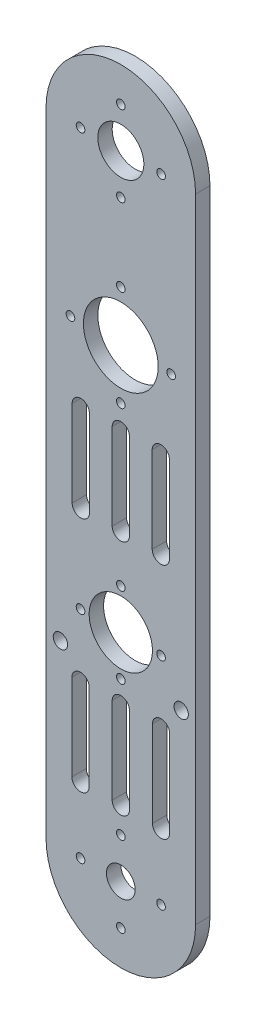
SolidWorks part; units mm, degrees
material "6061 合金"
ref_plane "前视基准面" through (0, 0, 0) normal (0, 0, 1) x (1, 0, 0)
ref_plane "上视基准面" through (0, 0, 0) normal (0, 1, 0) x (1, 0, 0)
ref_plane "右视基准面" through (0, 0, 0) normal (1, 0, 0) x (0, 0, -1)
other "质心 (COM)"
sketch "草图1" plane through (0, 0, 0) normal (0, 0, 1) x (1, 0, 0)
  line L0 (0, 0) -> (0, 110) construction
  line L1 (-26, 220) -> (-26, 0)
  line L4 (-58.7183, 110) -> (53.7841, 110) construction
  line L6 (26, 220) -> (26, 0)
  line L11 (0, 220) -> (0, 161.5) construction
  line L23 (21, 62) -> (21, 110) construction
  line L87 (-21, 62) -> (-21, 110) construction
  line L88 (0, 105.5) -> (0, 135.5) construction
  line L95 (-31.1577, 62) -> (32.7845, 62) construction
  line L99 (2.4, 40.8) -> (18.4, 52.8) construction
  line L100 (20, 40) -> (20, 52) construction
  line L101 (3, 39) -> (19, 39) construction
  line L102 (3.1504, 36.0012) -> (19.1504, 36.0012) construction
  line L103 (2.5504, 34.2012) -> (18.5504, 22.2012) construction
  line L104 (20.1504, 35.0012) -> (20.1504, 23.0012) construction
  line L111 (-2.5504, 34.2012) -> (-18.5504, 22.2012) construction
  line L112 (-20.1504, 35.0012) -> (-20.1504, 23.0012) construction
  line L113 (-3.1504, 36.0012) -> (-19.1504, 36.0012) construction
  line L119 (20, 136) -> (20, 148) construction
  line L120 (2.4, 136.8) -> (18.4, 148.8) construction
  line L121 (-20, 136) -> (-20, 148) construction
  line L122 (20, 131) -> (20, 119) construction
  line L123 (-2.4, 136.8) -> (-18.4, 148.8) construction
  line L124 (3, 132) -> (19, 132) construction
  line L125 (2.4, 130.2) -> (18.4, 118.2) construction
  line L126 (-3, 135) -> (-19, 135) construction
  line L127 (-3, 132) -> (-19, 132) construction
  line L128 (-20, 131) -> (-20, 119) construction
  line L129 (-2.4, 130.2) -> (-18.4, 118.2) construction
  line L130 (3, 135) -> (19, 135) construction
  line L137 (-3, 105.5) -> (-3, 135.5)
  line L140 (3, 105.5) -> (3, 135.5)
  line L143 (0, 23.0012) -> (0, 53.0012) construction
  line L145 (0, 23.0012) -> (0, 53.0012) construction
  line L146 (-3, 23.0012) -> (-3, 53.0012)
  line L147 (3, 23.0012) -> (3, 53.0012)
  line L148 (0, 23.0012) -> (-14, 23.0012) construction
  line L149 (-14, 23.0012) -> (-14, 53.0012) construction
  line L152 (-17, 23.0012) -> (-17, 53.0012)
  line L153 (-11, 23.0012) -> (-11, 53.0012)
  line L154 (14, 23.0012) -> (14, 53.0012) construction
  line L155 (17, 23.0012) -> (17, 53.0012)
  line L156 (11, 23.0012) -> (11, 53.0012)
  line L157 (0, 105.5) -> (0, 135.5) construction
  line L158 (0, 105.5) -> (-13.9136, 105.5) construction
  line L159 (-13.9136, 105.5) -> (-13.9136, 135.5) construction
  line L160 (-16.9136, 105.5) -> (-16.9136, 135.5)
  line L161 (-10.9136, 105.5) -> (-10.9136, 135.5)
  line L162 (13.9136, 105.5) -> (13.9136, 135.5) construction
  line L163 (16.9136, 105.5) -> (16.9136, 135.5)
  line L164 (10.9136, 105.5) -> (10.9136, 135.5)
  arc A0 (-26, 0) -> (26, 0) centre (0, 0) ccw
  circle A3 centre (0, 0) radius 5
  circle A5 centre (0, 0) radius 14 construction
  circle A6 centre (0, -14) radius 1.5
  circle A11 centre (0, 220) radius 22 construction
  circle A14 centre (0, 242) radius 2 construction
  circle A15 centre (0, 220) radius 8
  arc A16 (-26, 220) -> (26, 220) centre (0, 220) cw
  circle A22 centre (-14, 0) radius 1.5
  circle A23 centre (0, 14) radius 1.5
  circle A24 centre (14, 0) radius 1.5
  circle A28 centre (22, 220) radius 2 construction
  circle A29 centre (0, 198) radius 2 construction
  circle A30 centre (-22, 220) radius 2 construction
  circle A32 centre (-21, 62) radius 2.5
  circle A33 centre (21, 62) radius 2.5
  arc A106 (2.4, 40.8) -> (3, 39) centre (3, 40) ccw construction
  arc A107 (20, 52) -> (18.4, 52.8) centre (19, 52) ccw construction
  arc A108 (19, 39) -> (20, 40) centre (19, 40) ccw construction
  arc A109 (2.5504, 34.2012) -> (3.1504, 36.0012) centre (3.1504, 35.0012) cw construction
  arc A110 (20.1504, 23.0012) -> (18.5504, 22.2012) centre (19.1504, 23.0012) cw construction
  arc A111 (19.1504, 36.0012) -> (20.1504, 35.0012) centre (19.1504, 35.0012) cw construction
  arc A118 (-2.5504, 34.2012) -> (-3.1504, 36.0012) centre (-3.1504, 35.0012) ccw construction
  arc A119 (-20.1504, 23.0012) -> (-18.5504, 22.2012) centre (-19.1504, 23.0012) ccw construction
  arc A120 (-19.1504, 36.0012) -> (-20.1504, 35.0012) centre (-19.1504, 35.0012) ccw construction
  circle A143 centre (0, 161.5) radius 5.5 construction
  circle A148 centre (0, 75) radius 14 construction
  circle A149 centre (0, 89) radius 1.5
  circle A153 centre (0, 161.5) radius 13
  circle A154 centre (0, 75) radius 11
  circle A155 centre (0, 220) radius 14 construction
  circle A156 centre (0, 234) radius 1.5
  circle A157 centre (14, 220) radius 1.5
  circle A158 centre (0, 206) radius 1.5
  circle A159 centre (-14, 220) radius 1.5
  circle A160 centre (0, 161.5) radius 17.5 construction
  circle A165 centre (0, 179) radius 1.5
  circle A166 centre (17.5, 161.5) radius 1.5
  circle A167 centre (0, 144) radius 1.5
  circle A168 centre (-17.5, 161.5) radius 1.5
  circle A169 centre (14, 75) radius 1.5
  circle A170 centre (0, 61) radius 1.5
  circle A171 centre (-14, 75) radius 1.5
  arc A174 (-2.4, 136.8) -> (-3, 135) centre (-3, 136) cw construction
  arc A175 (-2.4, 130.2) -> (-3, 132) centre (-3, 131) ccw construction
  arc A176 (19, 135) -> (20, 136) centre (19, 136) ccw construction
  arc A177 (-20, 148) -> (-18.4, 148.8) centre (-19, 148) cw construction
  arc A178 (-20, 119) -> (-18.4, 118.2) centre (-19, 119) ccw construction
  arc A179 (2.4, 130.2) -> (3, 132) centre (3, 131) cw construction
  arc A180 (-19, 135) -> (-20, 136) centre (-19, 136) cw construction
  arc A181 (-19, 132) -> (-20, 131) centre (-19, 131) ccw construction
  arc A182 (20, 119) -> (18.4, 118.2) centre (19, 119) cw construction
  arc A183 (2.4, 136.8) -> (3, 135) centre (3, 136) ccw construction
  arc A184 (20, 148) -> (18.4, 148.8) centre (19, 148) ccw construction
  arc A185 (19, 132) -> (20, 131) centre (19, 131) cw construction
  arc A194 (-3, 23.0012) -> (3, 23.0012) centre (0, 23.0012) ccw
  arc A195 (3, 53.0012) -> (-3, 53.0012) centre (0, 53.0012) ccw
  arc A198 (-17, 23.0012) -> (-11, 23.0012) centre (-14, 23.0012) ccw
  arc A199 (-11, 53.0012) -> (-17, 53.0012) centre (-14, 53.0012) ccw
  arc A200 (17, 23.0012) -> (11, 23.0012) centre (14, 23.0012) cw
  arc A201 (11, 53.0012) -> (17, 53.0012) centre (14, 53.0012) cw
  arc A202 (-3, 105.5) -> (3, 105.5) centre (0, 105.5) ccw
  arc A203 (3, 135.5) -> (-3, 135.5) centre (0, 135.5) ccw
  arc A204 (-16.9136, 105.5) -> (-10.9136, 105.5) centre (-13.9136, 105.5) ccw
  arc A205 (-10.9136, 135.5) -> (-16.9136, 135.5) centre (-13.9136, 135.5) ccw
  arc A206 (16.9136, 105.5) -> (10.9136, 105.5) centre (13.9136, 105.5) cw
  arc A207 (10.9136, 135.5) -> (16.9136, 135.5) centre (13.9136, 135.5) cw
  point P48 (0, 220)
  point P51 (0, 0)
  point P55 (0, 220)
  point P58 (0, 120.5)
  point P65 (0, 161.5)
  point P72 (0, 75)
  point P133 (0, 38.0012)
  point P146 (-14, 38.0012)
  point P153 (14, 38.0012)
  point P170 (-13.9136, 120.5)
  point P177 (13.9136, 120.5)
  dimension "D1" = 4
  dimension "D2" = 4
  dimension "D6" = 110
  dimension "D7" = 26
  dimension "D8" = 4
  dimension "D9" = 48
  dimension "D11" = 58.5
  dimension "D12" = 4
  dimension "D14" = 14
  dimension "D3" = 5
  dimension "D4" = 75
  dimension "D5" = 4
  dimension "D10" = 5
  dimension "D13" = 48
extrude "凸台-拉伸1" add sketch "草图1" along normal blind 5
